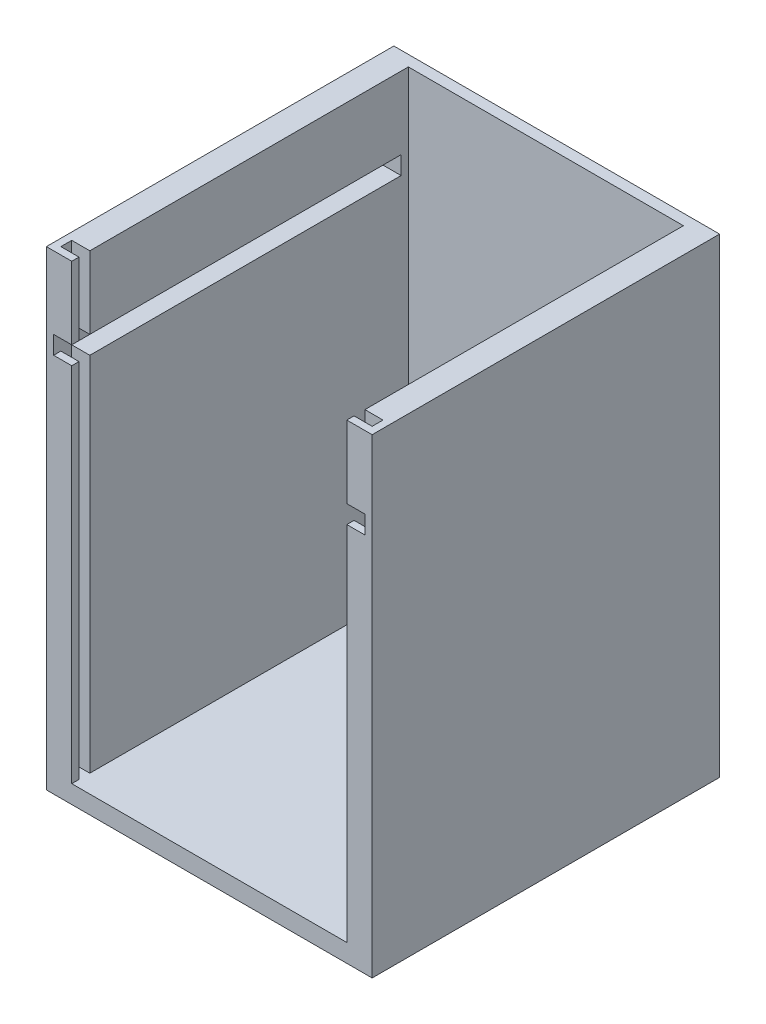
SolidWorks part; units mm, degrees
ref_plane "前基準面" through (0, 0, 0) normal (0, 0, 1) x (1, 0, 0)
ref_plane "上基準面" through (0, 0, 0) normal (0, 1, 0) x (1, 0, 0)
ref_plane "右基準面" through (0, 0, 0) normal (1, 0, 0) x (0, 0, -1)
sketch "草圖1" plane through (0, 0, 0) normal (0, 0, 1) x (1, 0, 0)
  line L1 (0, 0) -> (96, 0)
  line L2 (0, 0) -> (0, -130)
  line L3 (0, -130) -> (96, -130)
  line L4 (96, 0) -> (96, -130)
  dimension "D1" = 96
  dimension "D2" = 130
extrude "填料-伸長1" add sketch "草圖1" along normal blind 96
ref_plane "平面1" through (0, -125, 0) normal (0, -1, 0) x (-1, 0, 0)
sketch "草圖3" plane through (0, -125, 0) normal (0, -1, 0) x (-1, 0, 0)
  line L0 (0, -96) -> (-96, -96) construction
  line L1 (-86, -3) -> (-10, -3)
  line L2 (-86, -3) -> (-86, -96)
  line L3 (-86, -96) -> (-10, -96)
  line L4 (-10, -3) -> (-10, -96)
  line L5 (0, 0) -> (-96, 0) construction
  line L6 (-96, -96) -> (-96, 0) construction
  line L7 (0, -96) -> (0, 0) construction
  dimension "D1" = 3
  dimension "D2" = 10
  dimension "D3" = 10
extrude "除料-伸長1" cut sketch "草圖3" against normal blind 130
ref_plane "平面2" through (5, 0, 0) normal (-1, 0, 0) x (0, 0, 1)
ref_plane "平面3" through (0, 0, 94) normal (0, 0, 1) x (1, 0, 0)
sketch "草圖8" plane through (0, 0, 94) normal (0, 0, 1) x (1, 0, 0)
  line L0 (10, 0) -> (0, 0) construction
  line L1 (5, 0) -> (91, 0)
  line L2 (5, 0) -> (5, -125)
  line L3 (5, -125) -> (91, -125)
  line L4 (91, 0) -> (91, -125)
  dimension "D1" = 125
  dimension "D2" = 86
extrude "除料-伸長5" cut sketch "草圖8" against normal blind 3
sketch "草圖10" plane through (5, 0, 0) normal (-1, 0, 0) x (0, 0, 1)
  line L0 (96, 0) -> (96, -125) construction
  line L1 (96, -20) -> (5, -20)
  line L2 (96, -20) -> (96, -25)
  line L3 (96, -25) -> (5, -25)
  line L4 (5, -20) -> (5, -25)
  dimension "D1" = 91
  dimension "D2" = 5
  dimension "D3" = 20
extrude "除料-伸長7" cut sketch "草圖10" against normal blind 86
sketch "草圖12" plane through (5, 0, 0) normal (-1, 0, 0) x (0, 0, 1)
  line L0 (96, 0) -> (96, -130) construction
  line L1 (96, -1) -> (5, -1)
  line L2 (96, -1) -> (96, -4)
  line L3 (96, -4) -> (5, -4)
  line L4 (5, -1) -> (5, -4)
  line L5 (96, 0) -> (0, 0) construction
  dimension "D1" = 3
  dimension "D2" = 91
  dimension "D3" = 1
extrude "除料-伸長8" [suppressed] cut sketch "草圖12" against normal blind 86
sketch "草圖13" plane through (86, 0, 0) normal (-1, 0, 0) x (0, 0, 1)
  line L0 (3, 0) -> (3, -125) construction
  line L1 (96, -125) -> (3, -125)
  line L2 (96, -125) -> (96, -100)
  line L3 (96, -100) -> (3, -100)
  line L4 (3, -125) -> (3, -100)
  dimension "D1" = 25
extrude "除料-伸長9" [suppressed] cut sketch "草圖13" against normal blind 5
sketch "草圖15" plane through (0, 0, 0) normal (-1, 0, 0) x (0, 0, 1)
  line L1 (96, 0) -> (0, 0)
  line L2 (96, 0) -> (96, -130)
  line L3 (96, -130) -> (0, -130)
  line L4 (0, 0) -> (0, -130)
extrude "除料-伸長10" cut sketch "草圖15" against normal blind 3
sketch "草圖16" plane through (96, 0, 0) normal (1, 0, 0) x (0, 0, -1)
  line L1 (0, 0) -> (-96, 0)
  line L2 (0, 0) -> (0, -130)
  line L3 (0, -130) -> (-96, -130)
  line L4 (-96, 0) -> (-96, -130)
extrude "除料-伸長11" cut sketch "草圖16" against normal blind 3
